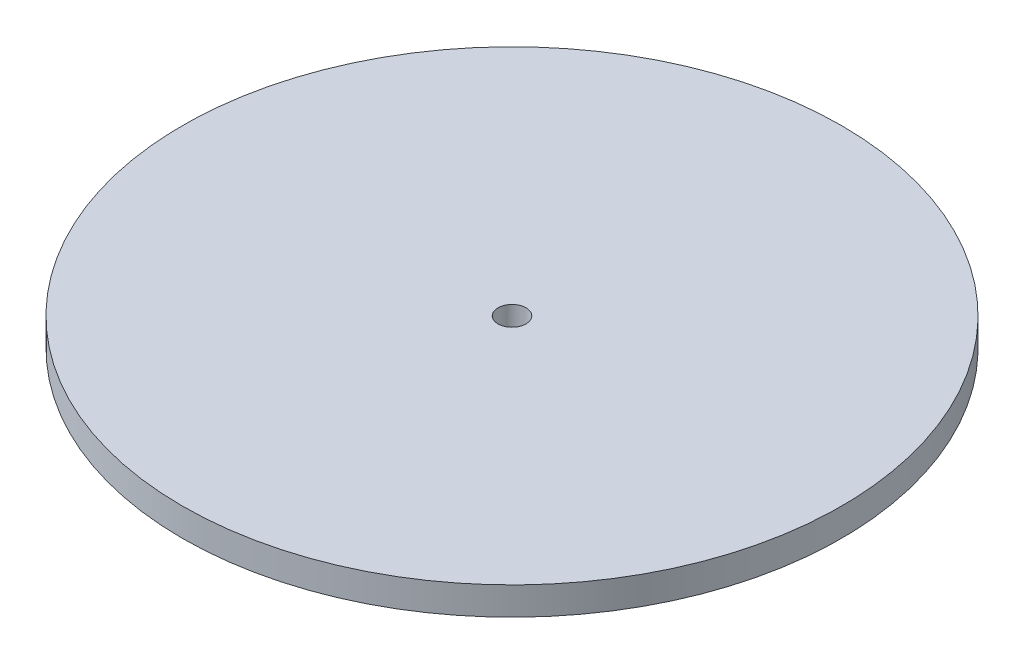
SolidWorks part; units mm, degrees
ref_plane "Front Plane" through (0, 0, 0) normal (0, 0, 1) x (1, 0, 0)
ref_plane "Top Plane" through (0, 0, 0) normal (0, 1, 0) x (1, 0, 0)
ref_plane "Right Plane" through (0, 0, 0) normal (1, 0, 0) x (0, 0, -1)
sketch "Sketch2" plane through (0, 0, 0) normal (0, 1, 0) x (1, 0, 0)
  circle A0 centre (0, 0) radius 74.7776
  dimension "D1" = 149.5552
extrude "Boss-Extrude1" add sketch "Sketch2" along normal mid plane 6.35
sketch "Sketch3" plane through (0, 3.175, 0) normal (0, 1, 0) x (1, 0, 0)
  circle A0 centre (0, 0) radius 3.175
  dimension "D1" = 6.35
extrude "Cut-Extrude1" cut sketch "Sketch3" against normal up to next
equation "\"diameter\"= 6 - 2 * .056"
equation "\"D1@Sketch2\"=\"diameter\""
